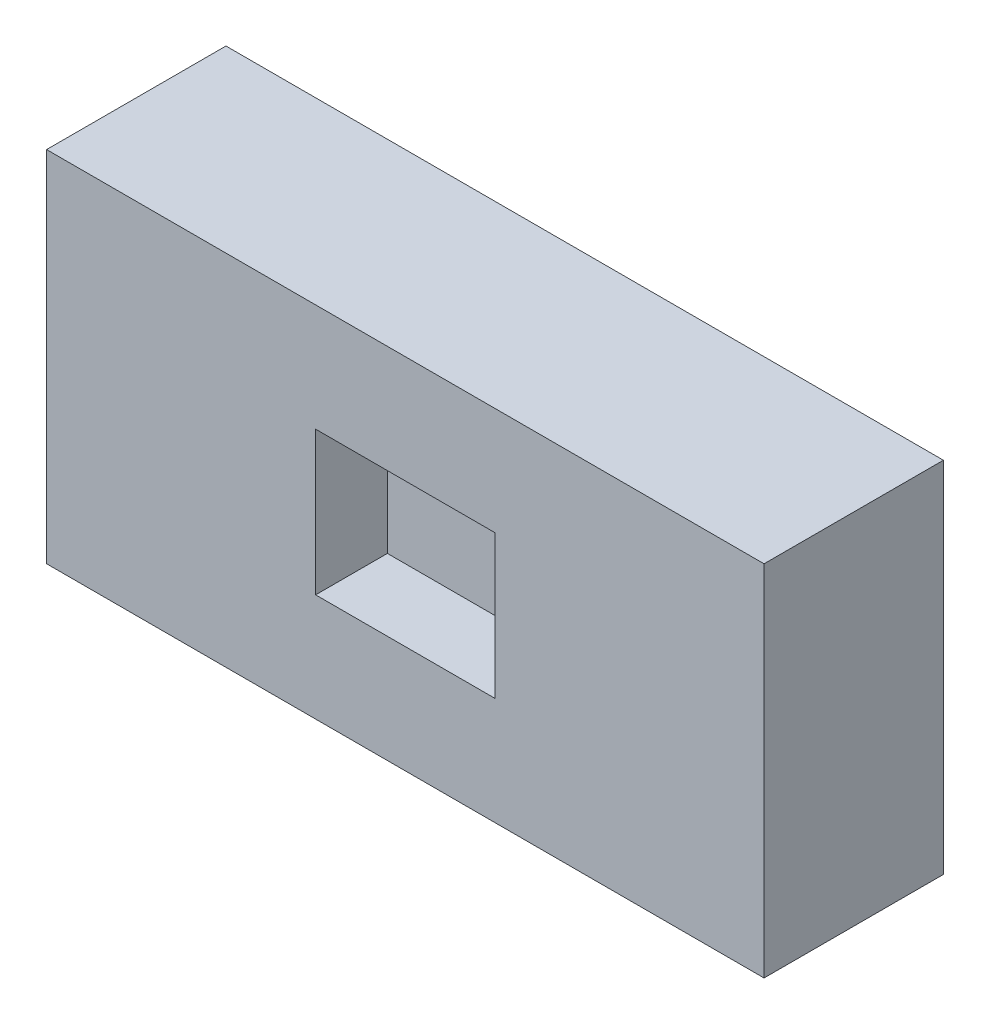
SolidWorks part; units mm, degrees
ref_plane "Front Plane" through (0, 0, 0) normal (0, 0, 1) x (1, 0, 0)
ref_plane "Top Plane" through (0, 0, 0) normal (0, 1, 0) x (1, 0, 0)
ref_plane "Right Plane" through (0, 0, 0) normal (1, 0, 0) x (0, 0, -1)
sketch "RectangleSketch" plane through (0, 0, 0) normal (0, 0, 1) x (1, 0, 0)
  line L1 (0, 0) -> (40, 0)
  line L2 (0, 0) -> (0, 20)
  line L3 (0, 20) -> (40, 20)
  line L4 (40, 0) -> (40, 20)
  dimension "width_mm" = 40
  dimension "height_mm" = 20
extrude "BlindBoss" add sketch "RectangleSketch" along normal blind 10 separate body
sketch "CutSketch" plane through (0, 0, 10) normal (0, 0, 1) x (1, 0, 0)
  line L1 (15, 6) -> (25, 6)
  line L2 (15, 6) -> (15, 14)
  line L3 (15, 14) -> (25, 14)
  line L4 (25, 6) -> (25, 14)
  dimension "cut_width_mm" = 10
  dimension "cut_height_mm" = 8
  dimension "cut_left_mm" = 15
  dimension "cut_bottom_mm" = 6
extrude "BlindCut" cut sketch "CutSketch" against normal blind 4
equation "\"cut_left_mm@CutSketch\" = (\"width_mm@RectangleSketch\" - \"cut_width_mm@CutSketch\") / 2"
equation "\"cut_bottom_mm@CutSketch\" = (\"height_mm@RectangleSketch\" - \"cut_height_mm@CutSketch\") / 2"
